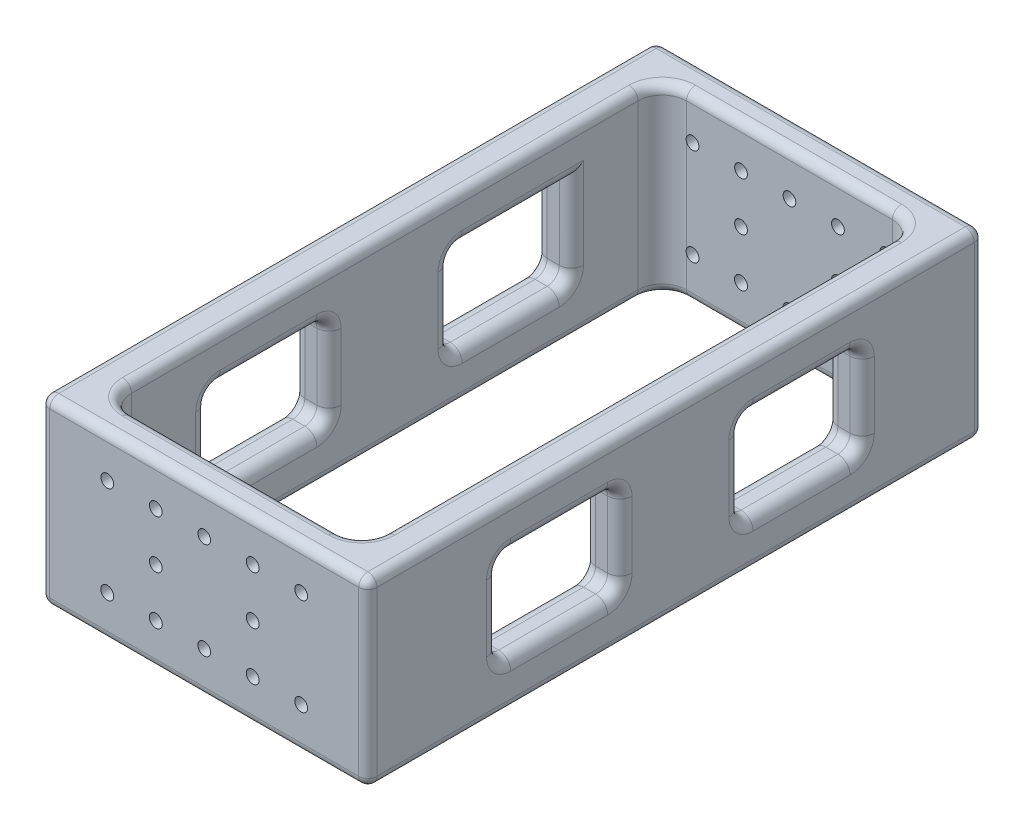
SolidWorks part; units mm, degrees
ref_plane "Front Plane" through (0, 0, 0) normal (0, 0, 1) x (1, 0, 0)
ref_plane "Top Plane" through (0, 0, 0) normal (0, 1, 0) x (1, 0, 0)
ref_plane "Right Plane" through (0, 0, 0) normal (1, 0, 0) x (0, 0, -1)
sketch "Sketch1" plane through (0, 0, 0) normal (0, 1, 0) x (1, 0, 0)
  line L1 (0, 0) -> (54, 0)
  line L2 (0, 0) -> (0, 101.6)
  line L3 (0, 101.6) -> (54, 101.6)
  line L4 (54, 0) -> (54, 101.6)
  dimension "D1" = 101.6
  dimension "D2" = 54
extrude "Boss-Extrude1" add sketch "Sketch1" along normal blind 49
sketch "Sketch2" plane through (0, 49, 0) normal (0, 1, 0) x (1, 0, 0)
  line L0 (54, 101.6) -> (0, 101.6) construction
  line L1 (6, 96.6) -> (48, 96.6)
  line L2 (6, 96.6) -> (6, 5)
  line L3 (6, 5) -> (48, 5)
  line L4 (48, 96.6) -> (48, 5)
  line L5 (0, 101.6) -> (0, 0) construction
  line L6 (54, 0) -> (54, 101.6) construction
  line L7 (0, 0) -> (54, 0) construction
  dimension "D1" = 5
  dimension "D2" = 6
  dimension "D3" = 6
  dimension "D4" = 5
extrude "Cut-Extrude1" cut sketch "Sketch2" against normal through all
sketch "Sketch4" plane through (0, 49, 0) normal (0, 1, 0) x (1, 0, 0)
  line L1 (0, 101.6) -> (54, 101.6)
  line L2 (0, 101.6) -> (0, 0)
  line L3 (0, 0) -> (54, 0)
  line L4 (54, 101.6) -> (54, 0)
extrude "Cut-Extrude3" cut sketch "Sketch4" against normal blind 19
sketch "Sketch6" plane through (0, 0, 0) normal (-1, 0, 0) x (0, 0, 1)
  line L0 (-101.6, 30) -> (-101.6, 0) construction
  line L1 (-81.6, 22.5) -> (-61.6, 22.5)
  line L2 (-81.6, 22.5) -> (-81.6, 7.5)
  line L3 (-81.6, 7.5) -> (-61.6, 7.5)
  line L4 (-61.6, 22.5) -> (-61.6, 7.5)
  line L5 (-101.6, 30) -> (0, 30) construction
  line L6 (-101.6, 0) -> (0, 0) construction
  line L8 (-41.6, 22.5) -> (-21.6, 22.5)
  line L9 (-41.6, 22.5) -> (-41.6, 7.5)
  line L10 (-41.6, 7.5) -> (-21.6, 7.5)
  line L11 (-21.6, 22.5) -> (-21.6, 7.5)
  dimension "D1" = 20
  dimension "D2" = 7.5
  dimension "D3" = 7.5
  dimension "D4" = 20
  dimension "D5" = 20
  dimension "D6" = 7.5
  dimension "D7" = 7.5
  dimension "D8" = 20
extrude "Cut-Extrude5" cut sketch "Sketch6" against normal through all
fillet "Fillet1" radius 2 47 edges at (48, 15, -61.6) (48, 15, -81.6) (54, 15, -81.6) (54, 15, -61.6) (48, 15, -21.6) (48, 15, -41.6) (54, 15, -41.6) (54, 15, -21.6) (6, 15, -41.6) (6, 15, -21.6) (0, 15, -21.6) (0, 15, -41.6) (6, 22.5, -71.6) (0, 22.5, -71.6) (6, 15, -81.6) (0, 15, -81.6) (48, 22.5, -71.6) (51, 22.5, -61.6) (54, 22.5, -71.6) (51, 22.5, -81.6) (48, 22.5, -31.6) (51, 22.5, -21.6) (54, 22.5, -31.6) (51, 22.5, -41.6) (6, 22.5, -31.6) (3, 22.5, -41.6) (0, 22.5, -31.6) (3, 22.5, -21.6) (48, 7.5, -71.6) (51, 7.5, -81.6) (54, 7.5, -71.6) (51, 7.5, -61.6) (48, 7.5, -31.6) (51, 7.5, -41.6) (54, 7.5, -31.6) (51, 7.5, -21.6) (6, 7.5, -31.6) (3, 7.5, -21.6) (0, 7.5, -31.6) (3, 7.5, -41.6) (6, 15, -61.6) (3, 22.5, -61.6) (0, 15, -61.6) (6, 7.5, -71.6) (3, 7.5, -61.6) (0, 7.5, -71.6) (3, 7.5, -81.6)
fillet "Fillet3" radius 4 2 edges at (48, 15, -5) (6, 15, -5)
fillet "Fillet4" radius 4 2 edges at (48, 15, -96.6) (6, 15, -96.6)
sketch "Sketch8" plane through (0, 0, -101.6) normal (0, 0, -1) x (-1, 0, 0)
  circle A0 centre (-43, 23) radius 1.05
  circle A1 centre (-35, 23) radius 1.05
  circle A2 centre (-27, 23) radius 1.05
  circle A3 centre (-19, 23) radius 1.05
  circle A4 centre (-11, 23) radius 1.05
  circle A5 centre (-35, 15) radius 1.05
  circle A6 centre (-19, 15) radius 1.05
  circle A7 centre (-43, 7) radius 1.05
  circle A8 centre (-35, 7) radius 1.05
  circle A9 centre (-27, 7) radius 1.05
  circle A10 centre (-19, 7) radius 1.0727
  circle A11 centre (-11, 7) radius 1.0654
extrude "Cut-Extrude7" cut sketch "Sketch8" against normal blind 10
sketch "Sketch9" plane through (0, 0, -5) normal (0, 0, -1) x (-1, 0, 0)
  circle A0 centre (-43, 23) radius 1.05
  circle A1 centre (-35, 23) radius 1.05
  circle A2 centre (-27, 23) radius 1.05
  circle A3 centre (-19, 23) radius 1.05
  circle A4 centre (-11, 23) radius 1.05
  circle A6 centre (-19, 15) radius 1.05
  circle A8 centre (-27, 7) radius 1.05
  circle A9 centre (-35, 15) radius 1.05
  circle A10 centre (-35, 7) radius 1.05
  circle A11 centre (-43, 7) radius 1.05
  circle A12 centre (-11, 7) radius 1.0654
  circle A13 centre (-19, 7) radius 1.0727
extrude "Cut-Extrude8" cut sketch "Sketch9" against normal blind 10
fillet "Fillet5" radius 1.5 28 edges at (27, 0, 0) (54, 0, -50.8) (27, 0, -101.6) (0, 0, -50.8) (46.8284, 0, -95.4284) (48, 0, -50.8) (46.8284, 0, -6.1716) (27, 0, -5) (7.1716, 0, -6.1716) (6, 0, -50.8) (7.1716, 0, -95.4284) (27, 0, -96.6) (46.8284, 30, -6.1716) (48, 30, -50.8) (46.8284, 30, -95.4284) (27, 30, -96.6) (7.1716, 30, -95.4284) (6, 30, -50.8) (7.1716, 30, -6.1716) (27, 30, -5) (27, 30, -101.6) (54, 30, -50.8) (27, 30, 0) (0, 30, -50.8) (54, 15, -101.6) (0, 15, -101.6) (0, 15, 0) (54, 15, 0)
